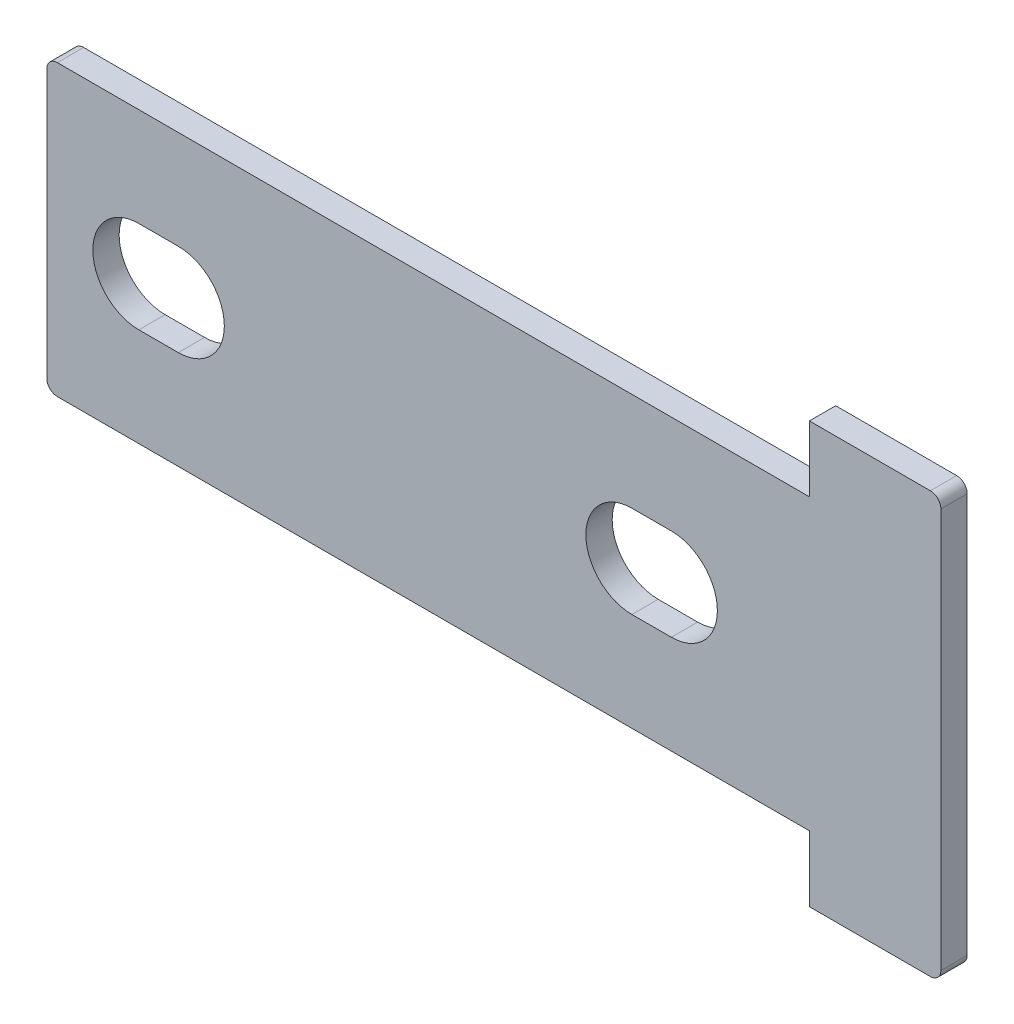
SolidWorks part; units mm, degrees
ref_plane "Front Plane" through (0, 0, 0) normal (0, 0, 1) x (1, 0, 0)
ref_plane "Top Plane" through (0, 0, 0) normal (0, 1, 0) x (1, 0, 0)
ref_plane "Right Plane" through (0, 0, 0) normal (1, 0, 0) x (0, 0, -1)
sketch "Szkic1" plane through (0, 0, 0) normal (0, 0, 1) x (1, 0, 0)
  line L0 (-3.1, -1.2673) -> (25.5, -1.2673)
  line L1 (25.5, -1.2673) -> (25.5, -3.7673)
  line L2 (25.5, -3.7673) -> (30.1, -3.7673)
  line L3 (30.5, -3.3673) -> (30.5, 11.8327)
  line L4 (30.1, 12.2327) -> (25.5, 12.2327)
  line L5 (25.5, 12.2327) -> (25.5, 9.7327)
  line L6 (25.5, 9.7327) -> (-3.1, 9.7327)
  line L7 (-3.5, 9.3327) -> (-3.5, -0.8673)
  line L8 (-3.5, 4.2327) -> (17, 4.2327) construction
  line L9 (18.75, 5.9827) -> (20.25, 5.9827)
  line L10 (18.75, 2.4827) -> (20.25, 2.4827)
  line L11 (22, 4.2327) -> (30.5, 4.2327) construction
  line L12 (0, 5.9827) -> (1.5, 5.9827)
  line L13 (0, 2.4827) -> (1.5, 2.4827)
  line L14 (0.75, 5.9827) -> (0.75, 2.4827) construction
  arc A0 (18.75, 5.9827) -> (18.75, 2.4827) centre (18.75, 4.2327) ccw
  arc A1 (20.25, 2.4827) -> (20.25, 5.9827) centre (20.25, 4.2327) ccw
  arc A2 (0, 5.9827) -> (0, 2.4827) centre (0, 4.2327) ccw
  arc A3 (1.5, 2.4827) -> (1.5, 5.9827) centre (1.5, 4.2327) ccw
  arc A4 (30.5, 11.8327) -> (30.1, 12.2327) centre (30.1, 11.8327) ccw
  arc A5 (30.1, -3.7673) -> (30.5, -3.3673) centre (30.1, -3.3673) ccw
  arc A6 (-3.5, -0.8673) -> (-3.1, -1.2673) centre (-3.1, -0.8673) ccw
  arc A7 (-3.1, 9.7327) -> (-3.5, 9.3327) centre (-3.1, 9.3327) ccw
  point P9 (19.5, 5.9827)
  dimension "D7" = 3.5
  dimension "D8" = 3.5
  dimension "D12" = 3.5
  dimension "D14" = 0.4
  dimension "D15" = 1.75
  dimension "D16" = 1.5
  dimension "D19" = 0.8
  dimension "D20" = 0.4
  dimension "D22" = 0.4
  dimension "D1" = 34
  dimension "D2" = 8
  dimension "D3" = 8
  dimension "D4" = 5
  dimension "D5" = 5
  dimension "D6" = 11
  dimension "D9" = 3.5
  dimension "D10" = 5
  dimension "D11" = 11
  dimension "D13" = 3.75
  dimension "D17" = 3.75
  dimension "D18" = 1.5
extrude "Dodanie-wyciągnięcie1" add sketch "Szkic1" along normal blind 1
